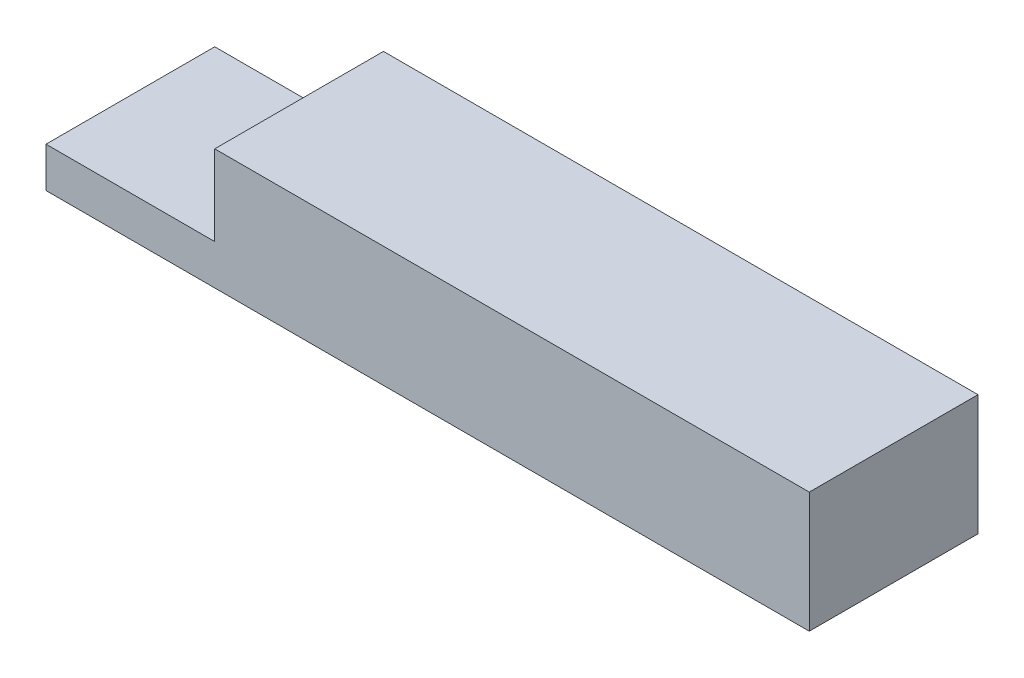
SolidWorks part; units mm, degrees
ref_plane "Front Plane" through (0, 0, 0) normal (0, 0, 1) x (1, 0, 0)
ref_plane "Top Plane" through (0, 0, 0) normal (0, 1, 0) x (1, 0, 0)
ref_plane "Right Plane" through (0, 0, 0) normal (1, 0, 0) x (0, 0, -1)
sketch "Sketch1" plane through (0, 0, 0) normal (0, 1, 0) x (1, 0, 0)
  line L0 (95, 0) -> (95, 21)
  line L1 (0, 0) -> (95, 0)
  line L2 (-11.55, 0) -> (11.55, 0) construction
  line L3 (95, 21) -> (0, 21)
  line L4 (0, -10.9612) -> (0, 10.9612) construction
  line L5 (0, 21) -> (0, 0)
  dimension "D1" = 21
  dimension "D2" = 21
extrude "Boss-Extrude2" add sketch "Sketch1" along normal blind 15
sketch "Sketch3" plane through (0, 15, 0) normal (0, 1, 0) x (1, 0, 0)
  line L0 (0, 0) -> (21, 0)
  line L1 (0, 0) -> (95, 0) construction
  line L2 (21, 0) -> (21, 21)
  line L3 (95, 21) -> (0, 21) construction
  line L4 (21, 21) -> (0, 21)
  line L5 (0, 21) -> (0, 0)
extrude "Cut-Extrude1" cut sketch "Sketch3" against normal blind 10
